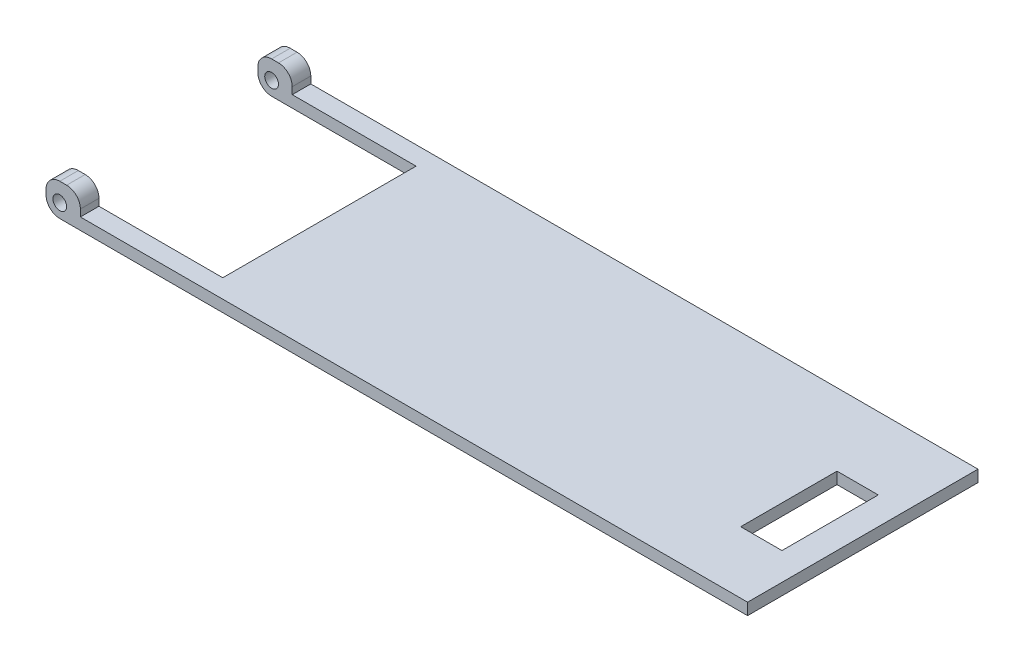
SolidWorks part; units mm, degrees
ref_plane "Front Plane" through (0, 0, 0) normal (0, 0, 1) x (1, 0, 0)
ref_plane "Top Plane" through (0, 0, 0) normal (0, 1, 0) x (1, 0, 0)
ref_plane "Right Plane" through (0, 0, 0) normal (1, 0, 0) x (0, 0, -1)
sketch "Sketch1" plane through (0, 0, 0) normal (0, 1, 0) x (1, 0, 0)
  line L1 (-51, -16.75) -> (51, -16.75)
  line L2 (-51, -16.75) -> (-51, 16.75)
  line L3 (-51, 16.75) -> (51, 16.75)
  line L4 (51, -16.75) -> (51, 16.75)
  line L5 (-51, -16.75) -> (51, 16.75) construction
  line L6 (-51, 16.75) -> (51, -16.75) construction
  point P0 (0, 0)
  dimension "D1" = 102
  dimension "D2" = 33.5
extrude "Boss-Extrude1" add sketch "Sketch1" along normal blind 1.7
sketch "Sketch2" plane through (0, 1.7, 0) normal (0, 1, 0) x (1, 0, 0)
  line L0 (-51, 16.75) -> (-51, -16.75) construction
  line L1 (-51, -14.05) -> (-28, -14.05)
  line L2 (-51, -14.05) -> (-51, 14.05)
  line L3 (-51, 14.05) -> (-28, 14.05)
  line L4 (-28, -14.05) -> (-28, 14.05)
  line L5 (-51, -16.75) -> (51, -16.75) construction
  line L6 (51, 16.75) -> (-51, 16.75) construction
  dimension "D1" = 2.7
  dimension "D2" = 2.7
  dimension "D3" = 23
extrude "Cut-Extrude1" cut sketch "Sketch2" against normal up to vertex (1.7 mm away)
sketch "Sketch4" plane through (0, 1.7, 0) normal (0, 1, 0) x (1, 0, 0)
  line L0 (-51, -16.75) -> (51, -16.75) construction
  line L1 (-51, -14.05) -> (-46, -14.05)
  line L2 (-51, -14.05) -> (-51, -16.75)
  line L3 (-51, -16.75) -> (-46, -16.75)
  line L4 (-46, -14.05) -> (-46, -16.75)
  dimension "D1" = 5
extrude "Boss-Extrude2" add sketch "Sketch4" along normal blind 3
sketch "Sketch5" plane through (0, 0, 16.75) normal (0, 0, 1) x (1, 0, 0)
  line L0 (-51, 0) -> (51, 0) construction
  line L1 (-51, 4.7) -> (-51, 0) construction
  circle A0 centre (-49, 2) radius 1
  dimension "D3" = 2
  dimension "D1" = 2
  dimension "D2" = 2
extrude "Cut-Extrude2" cut sketch "Sketch5" against normal up to vertex (2.7 mm away) contours A0
fillet "Fillet1" radius 2 3 edges at (-51, 0, 15.4) (-51, 4.7, 15.4) (-46, 4.7, 15.4)
ref_plane "Plane1" through (0, 0, 0) normal (0, 0, 1) x (1, 0, 0)
mirror "Mirror2" about plane through (0, 0, 0) normal (0, 0, 1) of "Boss-Extrude2", "Cut-Extrude2", "Fillet1"
sketch "Sketch10" plane through (0, 1.7, 0) normal (0, 1, 0) x (1, 0, 0)
  line L0 (51, -16.75) -> (51, 16.75) construction
  line L1 (41, -7.75) -> (47, -7.75)
  line L2 (41, -7.75) -> (41, 6.25)
  line L3 (41, 6.25) -> (47, 6.25)
  line L4 (47, -7.75) -> (47, 6.25)
  line L5 (41, -7.75) -> (47, 6.25) construction
  line L6 (41, 6.25) -> (47, -7.75) construction
  line L7 (51, 16.75) -> (-46, 16.75) construction
  point P0 (44, -0.75)
  dimension "D1" = 4
  dimension "D2" = 6
  dimension "D3" = 10.5
  dimension "D4" = 14
extrude "Cut-Extrude3" cut sketch "Sketch10" against normal up to vertex (1.7 mm away) up to point (51, 0, -16.75)
